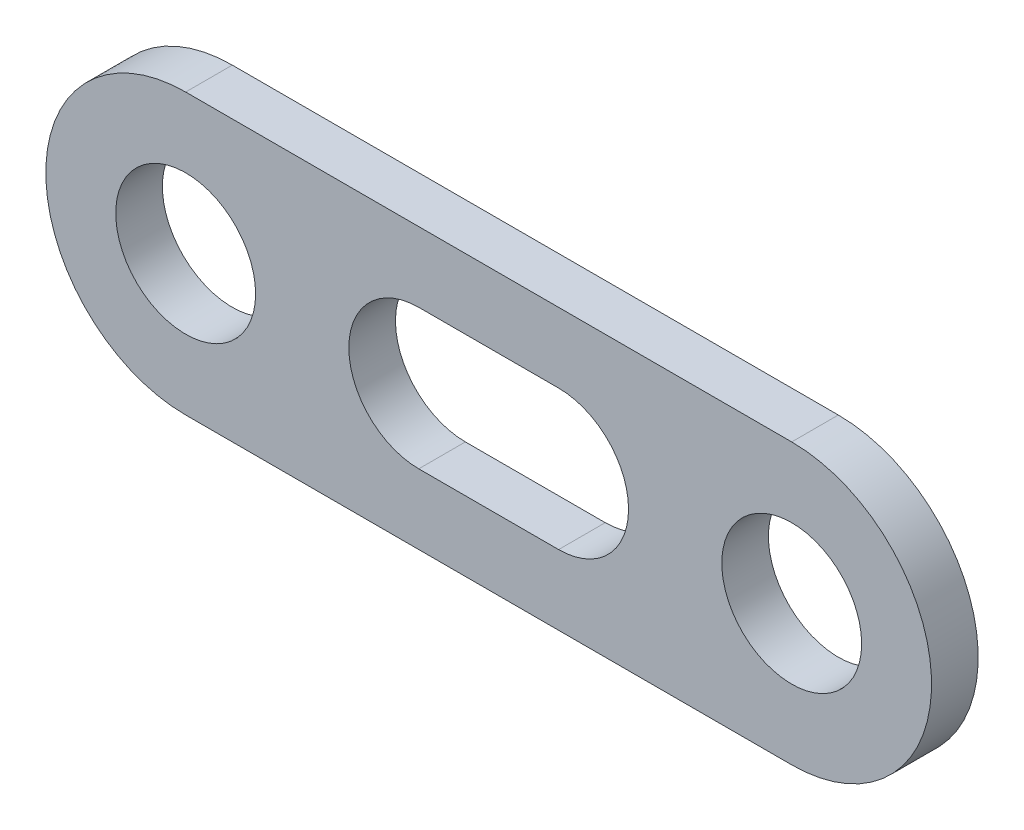
SolidWorks part; units mm, degrees
ref_plane "前视" through (0, 0, 0) normal (0, 0, 1) x (1, 0, 0)
ref_plane "上视" through (0, 0, 0) normal (0, 1, 0) x (1, 0, 0)
ref_plane "右视" through (0, 0, 0) normal (1, 0, 0) x (0, 0, -1)
sketch "草图2" plane through (0, 0, 0) normal (0, 0, 1) x (1, 0, 0)
  line L0 (0, 6) -> (26, 6)
  line L1 (0, -6) -> (26, -6)
  line L2 (10, 3) -> (16, 3)
  line L3 (10, -3) -> (16, -3)
  line L4 (-8.0174, 0) -> (37.0477, 0) construction
  arc A0 (0, 6) -> (0, -6) centre (0, 0) ccw
  arc A1 (26, -6) -> (26, 6) centre (26, 0) ccw
  circle A2 centre (0, 0) radius 3
  circle A3 centre (26, 0) radius 3
  arc A4 (10, 3) -> (10, -3) centre (10, 0) ccw
  arc A5 (16, -3) -> (16, 3) centre (16, 0) ccw
  dimension "D1" = 12
  dimension "D2" = 12
  dimension "D3" = 6
  dimension "D4" = 6
  dimension "D8" = 6
  dimension "D9" = 6
  dimension "D5" = 26
  dimension "D6" = 10
  dimension "D7" = 10
extrude "凸台-拉伸1" add sketch "草图2" along normal blind 2
